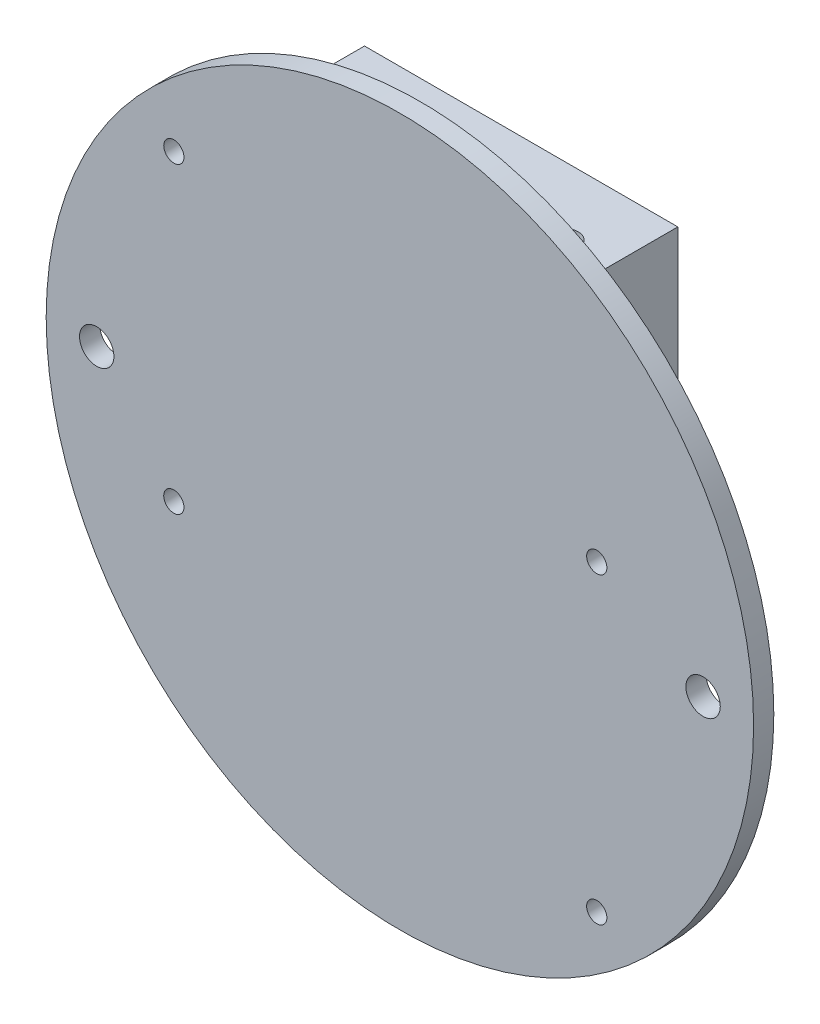
SolidWorks part; units mm, degrees
ref_plane "Front Plane" through (0, 0, 0) normal (0, 0, 1) x (1, 0, 0)
ref_plane "Top Plane" through (0, 0, 0) normal (0, 1, 0) x (1, 0, 0)
ref_plane "Right Plane" through (0, 0, 0) normal (1, 0, 0) x (0, 0, -1)
sketch "Sketch1" plane through (0, 0, 0) normal (0, 0, 1) x (1, 0, 0)
  circle A0 centre (0, 0) radius 35
  dimension "D1" = 70
extrude "Boss-Extrude1" add sketch "Sketch1" along normal blind 2 contours A0
sketch "Sketch2" plane through (0, 0, 0) normal (0, 0, -1) x (-1, 0, 0)
  line L51 (14.5, -8.5) -> (14.5, 26)
  line L52 (14.5, 26) -> (-14.5, 26)
  line L53 (-14.5, 26) -> (-14.5, -8.5)
  line L59 (15.5, -9.5) -> (15.5, 27)
  line L60 (15.5, 27) -> (-15.5, 27)
  line L61 (-15.5, 27) -> (-15.5, -9.5)
  line L64 (-14.5, -8.5) -> (14.5, -8.5)
  line L66 (-15.5, -9.5) -> (15.5, -9.5)
  dimension "D1" = 34.5
  dimension "D2" = 1
  dimension "D3" = 1
  dimension "D4" = 1
  dimension "D5" = 14.5
  dimension "D6" = 29
  dimension "D7" = 34.5
  dimension "D8" = 26
  dimension "D9" = 36.5
  dimension "D10" = 36.5
extrude "Boss-Extrude2" add sketch "Sketch2" along normal blind 10
sketch "Sketch3" plane through (0, 0, 0) normal (0, 0, -1) x (-1, 0, 0)
  circle A0 centre (22.3668, 20.53) radius 1
  circle A1 centre (22.37, -9.47) radius 1
  circle A2 centre (-19.48, 6.28) radius 1
  circle A3 centre (-19.48, -23.72) radius 1
  dimension "D1" = 2
  dimension "D2" = 2
  dimension "D3" = 2
  dimension "D4" = 2
  dimension "D5" = 30
  dimension "D6" = 22.37
  dimension "D7" = 20.53
  dimension "D8" = 30
  dimension "D9" = 19.48
  dimension "D10" = 6.28
extrude "Cut-Extrude1" cut sketch "Sketch3" against normal blind 10
sketch "Sketch5" plane through (0, -8.5, 0) normal (0, 1, 0) x (1, 0, 0)
  line L1 (35, 0) -> (-35, 0) construction
  line L3 (-15.5, 0) -> (15.5, 0) construction
  circle A0 centre (-11, 3.25) radius 1.4
  circle A1 centre (11, 3.25) radius 1.4
  dimension "D1" = 2.8
  dimension "D2" = 2.8
  dimension "D3" = 11
  dimension "D4" = 3.25
  dimension "D5" = 11
  dimension "D6" = 3.25
extrude "Cut-Extrude2" cut sketch "Sketch5" against normal up to surface and the other way up to surface up to face at (0, -9.5, -5) other way up to face at (0, 27, -5)
sketch "Sketch6" plane through (0, 0, 2) normal (0, 0, 1) x (1, 0, 0)
  circle A0 centre (30, 0) radius 1.7
  circle A1 centre (-30, 0) radius 1.7
  dimension "D1" = 3.4
  dimension "D2" = 3.4
  dimension "D3" = 30
  dimension "D4" = 30
extrude "Cut-Extrude3" cut sketch "Sketch6" against normal through all
